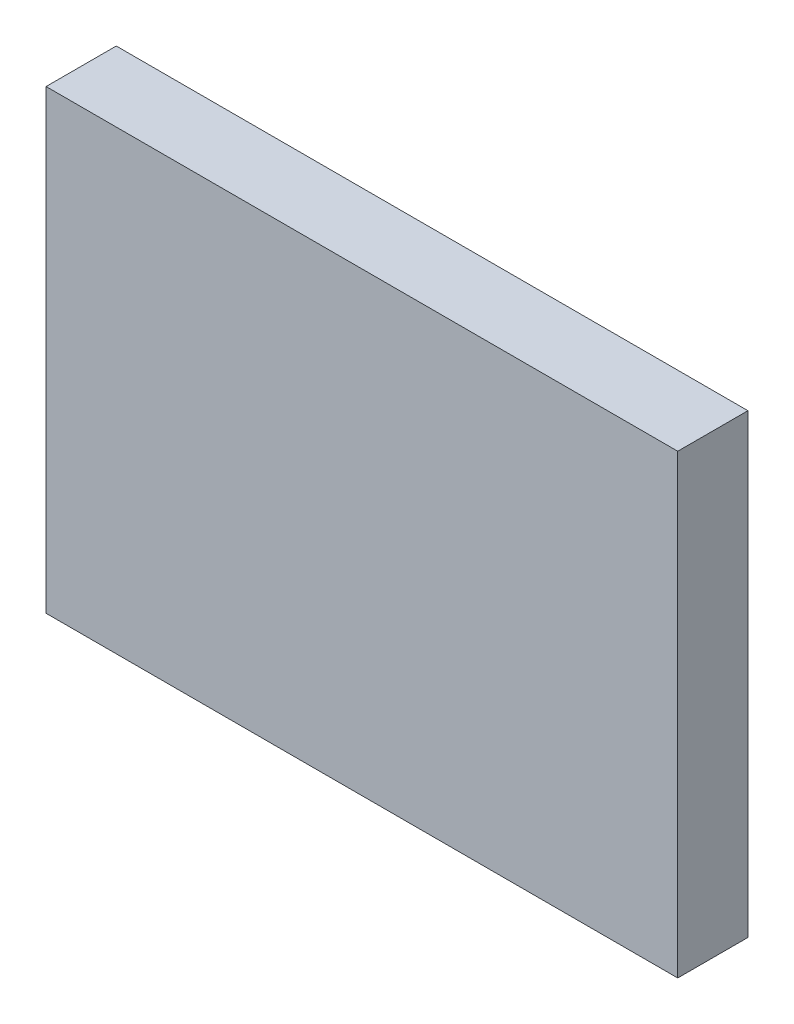
SolidWorks part; units mm, degrees
ref_plane "Front Plane" through (0, 0, 0) normal (0, 0, 1) x (1, 0, 0)
ref_plane "Top Plane" through (0, 0, 0) normal (0, 1, 0) x (1, 0, 0)
ref_plane "Right Plane" through (0, 0, 0) normal (1, 0, 0) x (0, 0, -1)
sketch "Sketch1" plane through (0, 0, 0) normal (0, 0, 1) x (1, 0, 0)
  line L1 (-9, -6.5) -> (9, -6.5)
  line L2 (-9, -6.5) -> (-9, 6.5)
  line L3 (-9, 6.5) -> (9, 6.5)
  line L4 (9, -6.5) -> (9, 6.5)
extrude "REFERENCE_ENVELOPE_NOT_MANUFACTURING" add sketch "Sketch1" along normal blind 2 from offset 0
